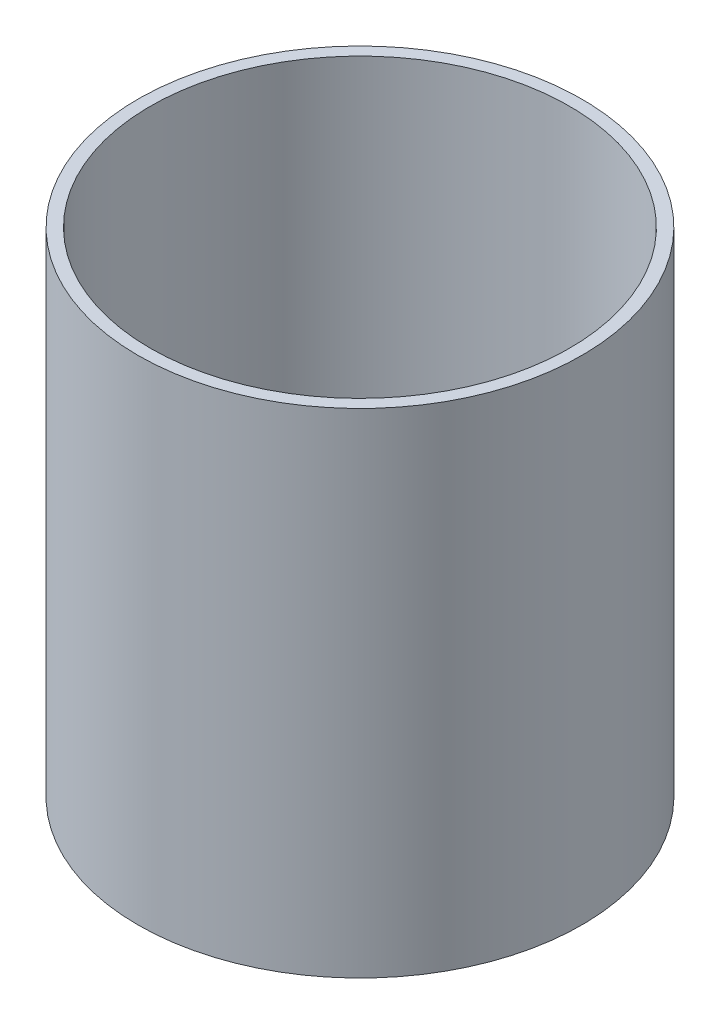
SolidWorks part; units mm, degrees
ref_plane "Front Plane" through (0, 0, 0) normal (0, 0, 1) x (1, 0, 0)
ref_plane "Top Plane" through (0, 0, 0) normal (0, 1, 0) x (1, 0, 0)
ref_plane "Right Plane" through (0, 0, 0) normal (1, 0, 0) x (0, 0, -1)
sketch "Sketch1" plane through (0, 0, 0) normal (0, 1, 0) x (1, 0, 0)
  circle A0 centre (0, 0) radius 22.5
  circle A1 centre (0, 0) radius 21.25
  dimension "D1" = 45
  dimension "D2" = 42.5
extrude "Boss-Extrude1" add sketch "Sketch1" along normal blind 50
